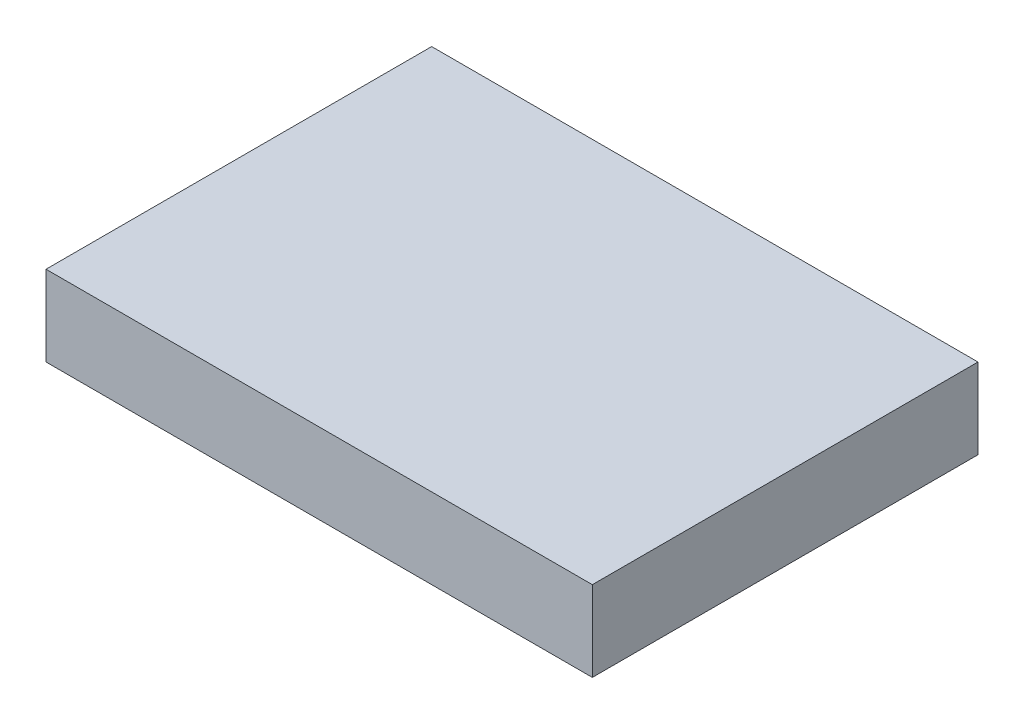
SolidWorks part; units mm, degrees
ref_plane "Plano frontal" through (0, 0, 0) normal (0, 0, 1) x (1, 0, 0)
ref_plane "Plano superior" through (0, 0, 0) normal (0, 1, 0) x (1, 0, 0)
ref_plane "Plano direito" through (0, 0, 0) normal (1, 0, 0) x (0, 0, -1)
sketch "Esboço1" plane through (0, 0, 0) normal (0, 1, 0) x (1, 0, 0)
  line L1 (-17, -12) -> (17, -12)
  line L2 (-17, -12) -> (-17, 12)
  line L3 (-17, 12) -> (17, 12)
  line L4 (17, -12) -> (17, 12)
  line L5 (-17, -12) -> (17, 12) construction
  line L6 (-17, 12) -> (17, -12) construction
  point P0 (0, 0)
  dimension "D1" = 34
  dimension "D2" = 24
extrude "Ressalto-extrusão1" add sketch "Esboço1" along normal blind 5
